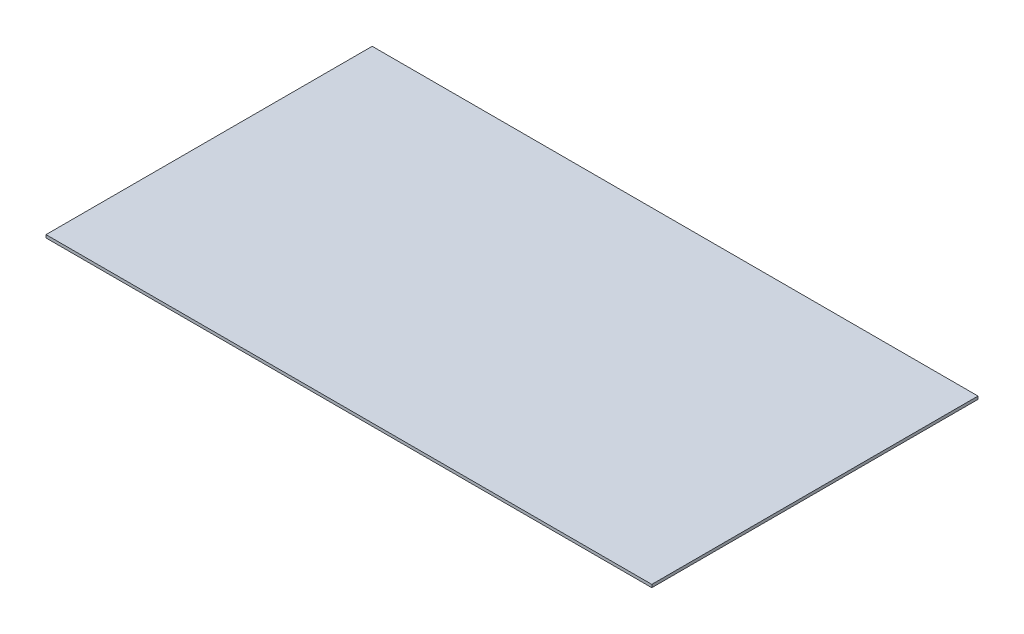
SolidWorks part; units mm, degrees
ref_plane "Front Plane" through (0, 0, 0) normal (0, 0, 1) x (1, 0, 0)
ref_plane "Top Plane" through (0, 0, 0) normal (0, 1, 0) x (1, 0, 0)
ref_plane "Right Plane" through (0, 0, 0) normal (1, 0, 0) x (0, 0, -1)
sketch "Sketch1" plane through (0, 0, 0) normal (0, 1, 0) x (1, 0, 0)
  line L1 (0, 0) -> (660.4, 0)
  line L2 (0, 0) -> (0, 355.6)
  line L3 (0, 355.6) -> (660.4, 355.6)
  line L4 (660.4, 0) -> (660.4, 355.6)
  dimension "D1" = 660.4
  dimension "D2" = 355.6
extrude "Boss-Extrude1" add sketch "Sketch1" along normal blind 3.175
